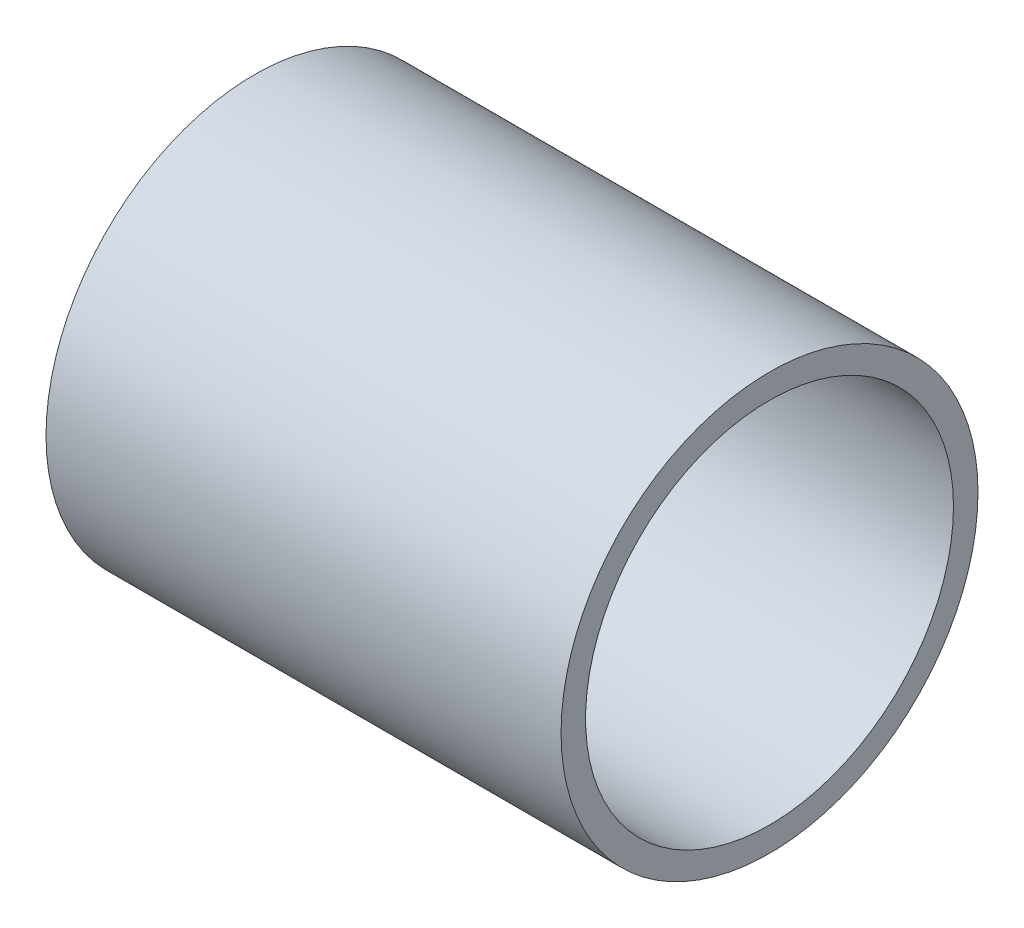
SolidWorks part; units mm, degrees
ref_plane "Front Plane" through (0, 0, 0) normal (0, 0, 1) x (1, 0, 0)
ref_plane "Top Plane" through (0, 0, 0) normal (0, 1, 0) x (1, 0, 0)
ref_plane "Right Plane" through (0, 0, 0) normal (1, 0, 0) x (0, 0, -1)
sketch "Sketch1" plane through (0, 0, 0) normal (1, 0, 0) x (0, 0, -1)
  circle A0 centre (0, 0) radius 75
  dimension "D1" = 150
extrude "Boss-Extrude1" add sketch "Sketch1" along normal blind 200
shell "Shell1" thickness 10
